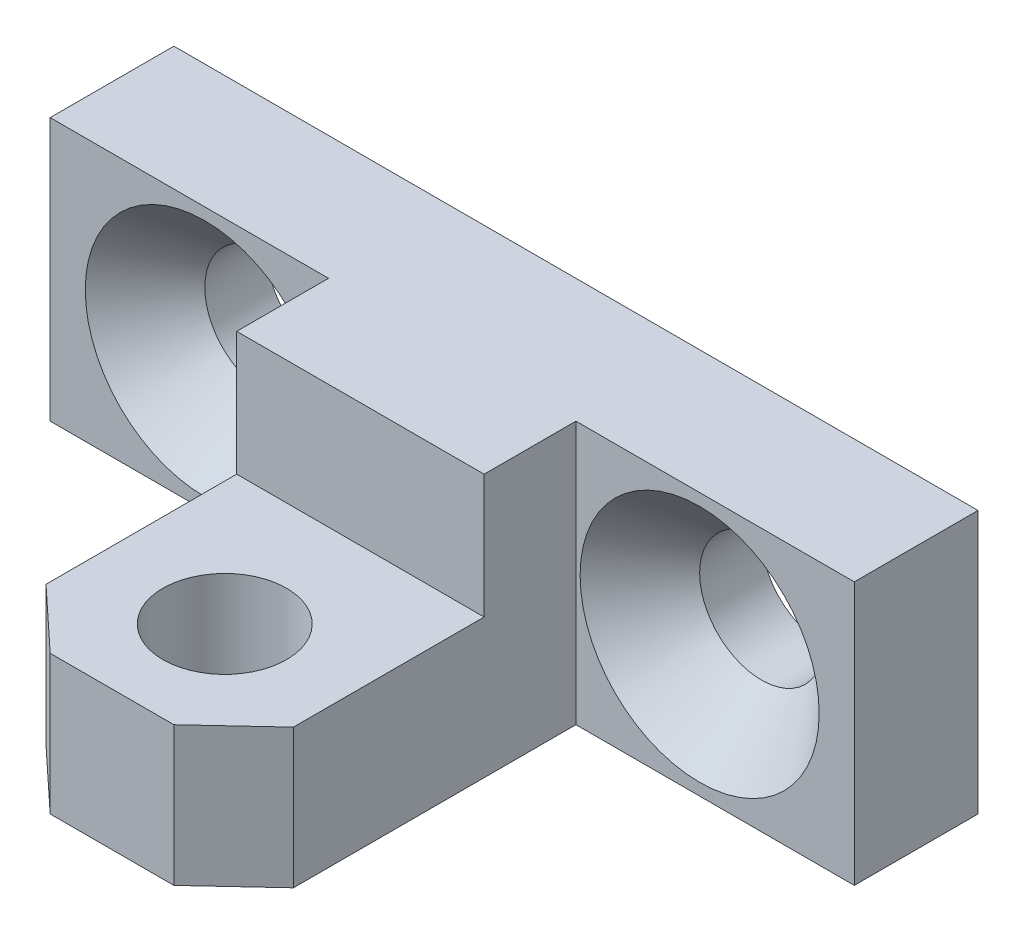
SolidWorks part; units mm, degrees
ref_plane "Спереди" through (0, 0, 0) normal (0, 0, 1) x (1, 0, 0)
ref_plane "Сверху" through (0, 0, 0) normal (0, 1, 0) x (1, 0, 0)
ref_plane "Справа" through (0, 0, 0) normal (1, 0, 0) x (0, 0, -1)
sketch "Эскиз1" plane through (0, 0, 0) normal (0, 0, 1) x (1, 0, 0)
  line L1 (0, 0) -> (26, 0)
  line L2 (0, 0) -> (0, -8.5)
  line L3 (0, -8.5) -> (26, -8.5)
  line L4 (26, 0) -> (26, -8.5)
extrude "Вытянуть1" add sketch "Эскиз1" along normal blind 15
sketch "Эскиз2" plane through (0, 0, 0) normal (0, 1, 0) x (1, 0, 0)
  line L0 (13, 0) -> (13, 9.2119) construction
  line L2 (0, -15) -> (0, 0) construction
  line L3 (0, -4) -> (9, -4)
  line L4 (0, -4) -> (0, -21.1515)
  line L5 (0, -21.1515) -> (9, -21.1515)
  line L6 (9, -4) -> (9, -21.1515)
  line L7 (26, 0) -> (0, 0) construction
  line L8 (17, -4) -> (17, -21.1515)
  line L9 (26, -21.1515) -> (17, -21.1515)
  line L10 (26, -4) -> (26, -21.1515)
  line L11 (26, -4) -> (17, -4)
  dimension "D1" = 4
extrude "Вытянуть2" cut sketch "Эскиз2" against normal blind 20
chamfer "Фаска1" distance 2 angle 43 2 edges at (17, -4.25, 15) (9, -4.25, 15)
sketch "Эскиз3" plane through (0, 0, 0) normal (0, 0, -1) x (-1, 0, 0)
  circle A0 centre (-21, -4.25) radius 2
  circle A1 centre (-5, -4.2515) radius 2
extrude "Вырез-Вытянуть1" cut sketch "Эскиз3" against normal through all
chamfer "Фаска2" distance 2 angle 43 2 edges at (19, -4.25, 4) (3, -4.2515, 4)
sketch "Эскиз4" plane through (0, 0, 0) normal (0, 1, 0) x (1, 0, 0)
  line L1 (7.3896, -6.9688) -> (18.7368, -6.9688)
  line L2 (7.3896, -6.9688) -> (7.3896, -15.8517)
  line L3 (7.3896, -15.8517) -> (18.7368, -15.8517)
  line L4 (18.7368, -6.9688) -> (18.7368, -15.8517)
extrude "Вырез-Вытянуть2" cut sketch "Эскиз4" against normal blind 4
sketch "Эскиз5" plane through (0, -4, 0) normal (0, 1, 0) x (1, 0, 0)
  circle A0 centre (13, -11.3557) radius 2
extrude "Вырез-Вытянуть3" cut sketch "Эскиз5" against normal through all
